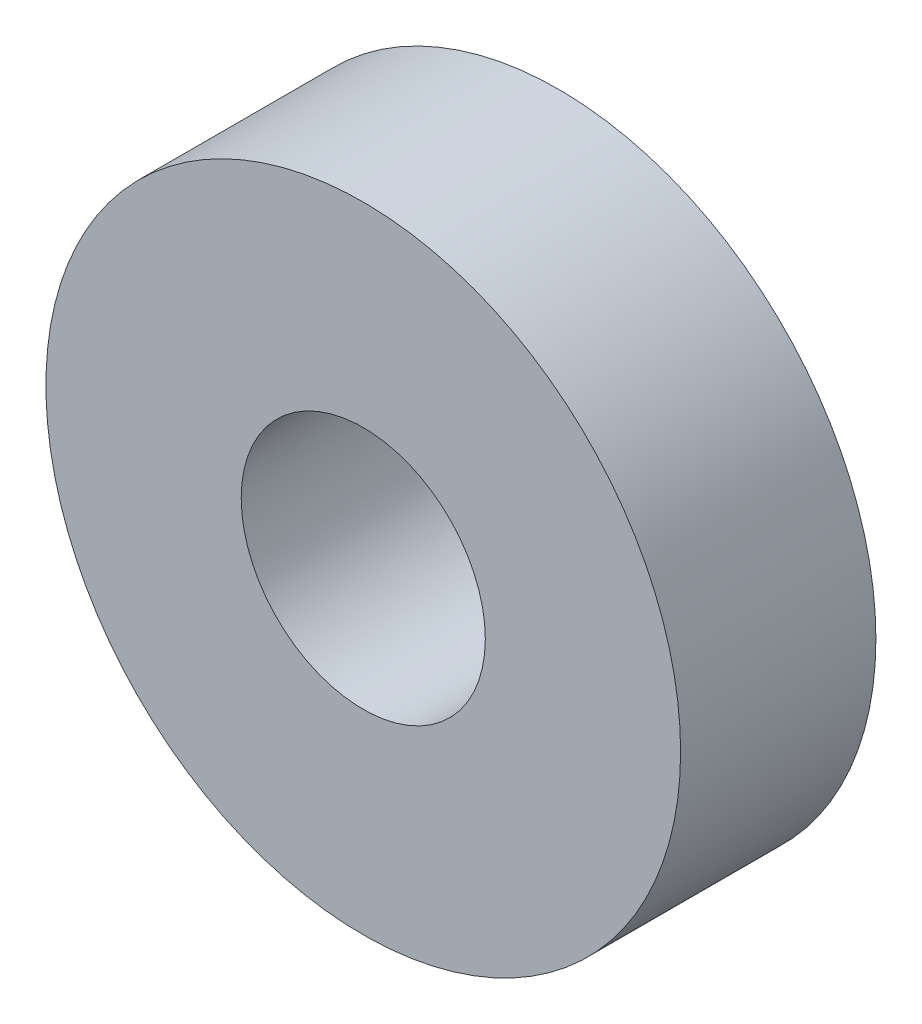
SolidWorks part; units mm, degrees
ref_plane "Front Plane" through (0, 0, 0) normal (0, 0, 1) x (1, 0, 0)
ref_plane "Top Plane" through (0, 0, 0) normal (0, 1, 0) x (1, 0, 0)
ref_plane "Right Plane" through (0, 0, 0) normal (1, 0, 0) x (0, 0, -1)
sketch "Sketch1" plane through (0, 0, 0) normal (0, 0, 1) x (1, 0, 0)
  circle A0 centre (0, 0) radius 6.5
  circle A1 centre (0, 0) radius 2.5
  dimension "D1" = 13
  dimension "D2" = 5
extrude "Boss-Extrude1" add sketch "Sketch1" along normal blind 4
